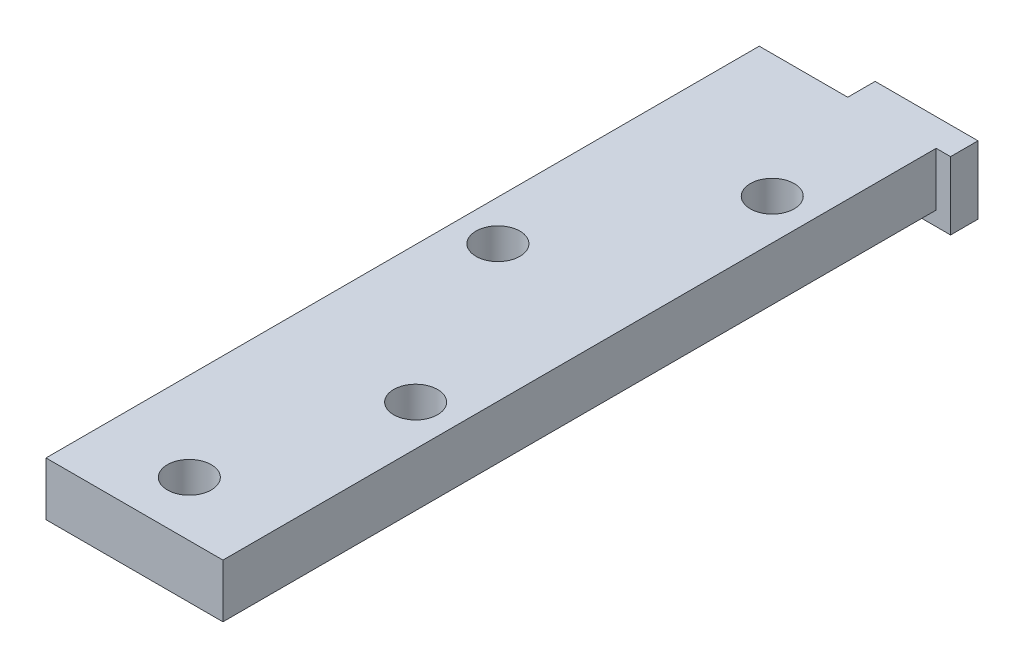
SolidWorks part; units mm, degrees
material "PLA"
ref_plane "前视基准面" through (0, 0, 0) normal (0, 0, 1) x (1, 0, 0)
ref_plane "上视基准面" through (0, 0, 0) normal (0, 1, 0) x (1, 0, 0)
ref_plane "右视基准面" through (0, 0, 0) normal (1, 0, 0) x (0, 0, -1)
sketch "草图1" plane through (0, 0, 0) normal (0, 0, 1) x (1, 0, 0)
  line L0 (0, 3) -> (0, -3)
  line L1 (7.5, -3) -> (0, -3)
  line L2 (7.5, -3) -> (7.5, 3)
  line L3 (7.5, 3) -> (0, 3)
  line L4 (-7.5, -3) -> (-7.5, 3) construction
  line L5 (7.5, -3) -> (-7.5, 3) construction
  line L6 (7.5, 3) -> (-7.5, -3) construction
  point P0 (0, 0)
  dimension "D1" = 15
  dimension "D2" = 6
extrude "凸台-拉伸1" add sketch "草图1" along normal blind 2
sketch "草图2" plane through (0, 0, 2) normal (0, 0, 1) x (1, 0, 0)
  line L1 (6.45, -1.95) -> (-6.45, -1.95)
  line L2 (6.45, -1.95) -> (6.45, 1.95)
  line L3 (6.45, 1.95) -> (-6.45, 1.95)
  line L4 (-6.45, -1.95) -> (-6.45, 1.95)
  line L5 (6.45, -1.95) -> (-6.45, 1.95) construction
  line L6 (6.45, 1.95) -> (-6.45, -1.95) construction
  point P0 (0, 0)
  dimension "D1" = 12.9
  dimension "D2" = 3.9
extrude "凸台-拉伸2" add sketch "草图2" along normal blind 52
sketch "草图3" plane through (0, -1.95, 0) normal (0, -1, 0) x (1, 0, 0)
  line L0 (3.5, 2) -> (3.5, 37) construction
  line L1 (0, 2) -> (6.45, 2) construction
  line L2 (7.5, 24.6481) -> (7.5, 6.8705) construction
  line L3 (-7.5, 24.6481) -> (-7.5, 6.3884) construction
  line L4 (0, 2) -> (7.5, 2) construction
  circle A0 centre (3.5, 37) radius 1.6
  circle A1 centre (3.5, 11) radius 1.6
  circle A2 centre (-3.5, 24) radius 1.6
  circle A3 centre (0, 50) radius 1.6
  dimension "D1" = 3.2
  dimension "D2" = 7.5
  dimension "D3" = 7.5
  dimension "D4" = 4
  dimension "D5" = 8
  dimension "D6" = 9
  dimension "D7" = 26
  dimension "D8" = 13
  dimension "D9" = 13
  dimension "D10" = 3.5
extrude "切除-拉伸1" cut sketch "草图3" against normal blind 356
sketch "草图4" plane through (0, 0, 2) normal (0, 0, 1) x (1, 0, 0)
  line L0 (0, 1.95) -> (7.5, 1.95)
  line L1 (7.5, -3) -> (7.5, 3) construction
  line L2 (7.5, 1.95) -> (7.5, 3)
  line L3 (7.5, 3) -> (0, 3)
  line L4 (0, 3) -> (0, 1.95)
extrude "切除-拉伸2" cut sketch "草图4" against normal blind 10
